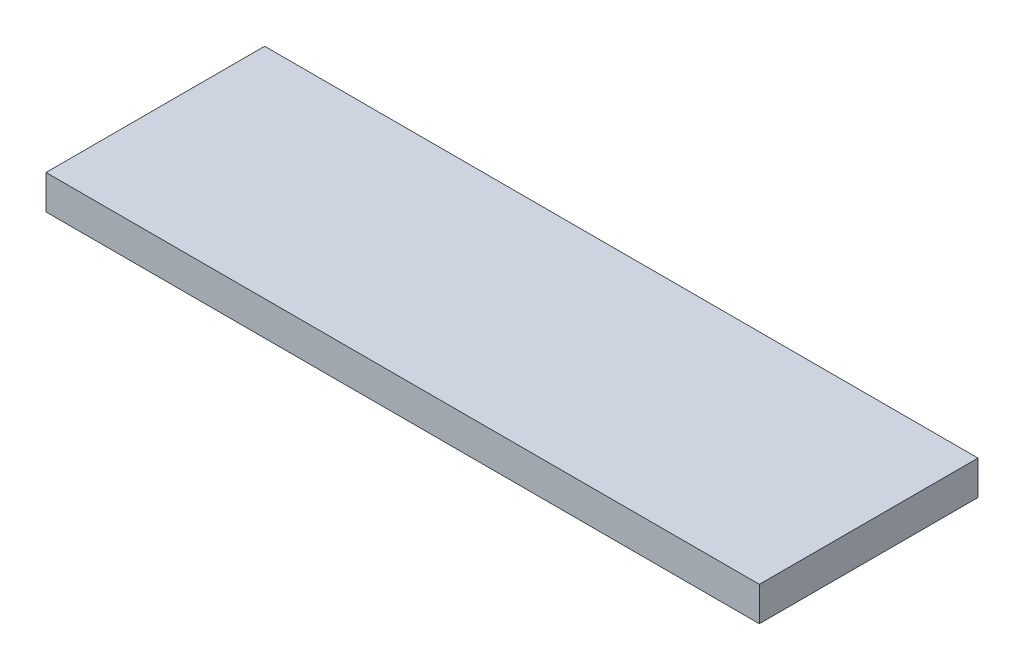
SolidWorks part; units mm, degrees
ref_plane "Front Plane" through (0, 0, 0) normal (0, 0, 1) x (1, 0, 0)
ref_plane "Top Plane" through (0, 0, 0) normal (0, 1, 0) x (1, 0, 0)
ref_plane "Right Plane" through (0, 0, 0) normal (1, 0, 0) x (0, 0, -1)
sketch "Sketch1" plane through (0, 0, 0) normal (0, 1, 0) x (1, 0, 0)
  line L1 (0, 0) -> (132.588, 0)
  line L2 (0, 0) -> (0, 40.64)
  line L3 (0, 40.64) -> (132.588, 40.64)
  line L4 (132.588, 0) -> (132.588, 40.64)
  dimension "D1" = 132.588
  dimension "D2" = 40.64
extrude "Boss-Extrude1" add sketch "Sketch1" along normal blind 6.35
